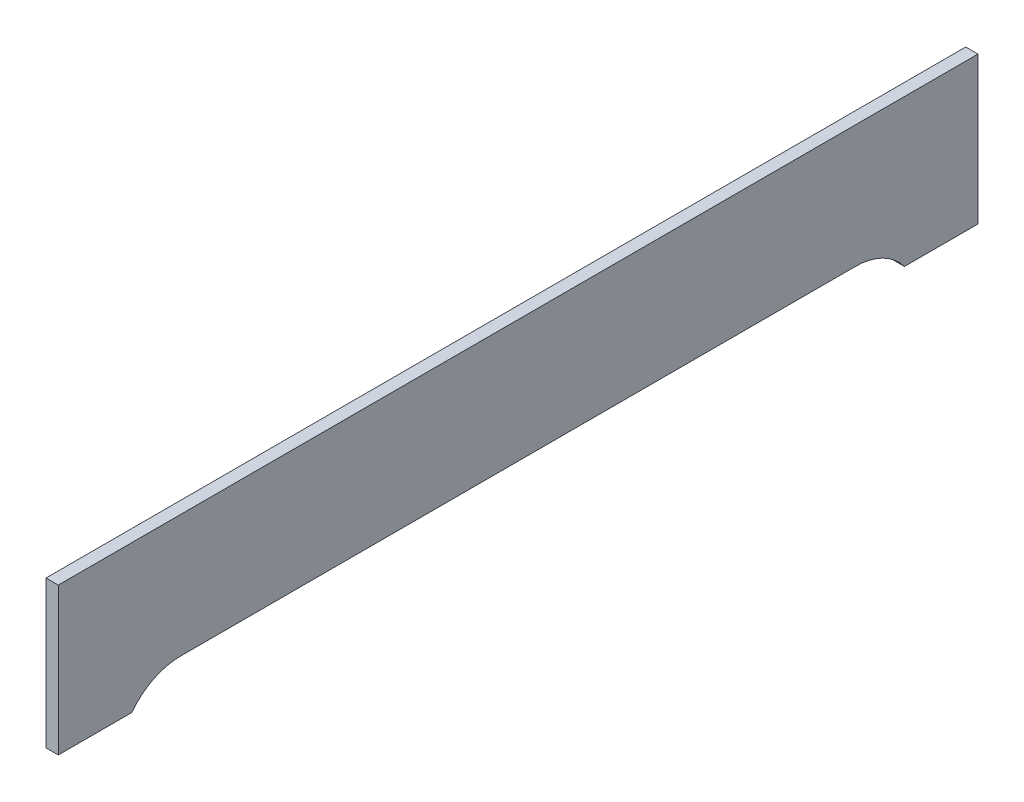
SolidWorks part; units mm, degrees
ref_plane "Front Plane" through (0, 0, 0) normal (0, 0, 1) x (1, 0, 0)
ref_plane "Top Plane" through (0, 0, 0) normal (0, 1, 0) x (1, 0, 0)
ref_plane "Right Plane" through (0, 0, 0) normal (1, 0, 0) x (0, 0, -1)
sketch "Sketch1" plane through (0, 0, 0) normal (1, 0, 0) x (0, 0, -1)
  line L0 (0, 0) -> (0, -10)
  line L1 (50, 0) -> (325, 0)
  line L2 (0, 0) -> (0, 50)
  line L3 (0, 50) -> (375, 50)
  line L4 (375, 0) -> (375, 50)
  line L5 (0, -10) -> (30, -10)
  line L6 (375, 0) -> (375, -10)
  line L7 (375, -10) -> (345, -10)
  arc A0 (30, -10) -> (50, 0) centre (50, -25) cw
  arc A1 (345, -10) -> (325, 0) centre (325, -25) ccw
  point P12 (0, 0)
  dimension "D5" = 25
  dimension "D7" = 25
  dimension "D1" = 375
  dimension "D2" = 50
  dimension "D3" = 10
  dimension "D4" = 30
  dimension "D6" = 10
  dimension "D8" = 10
  dimension "D9" = 30
  dimension "D10" = 10
extrude "Boss-Extrude1" add sketch "Sketch1" along normal blind 5
